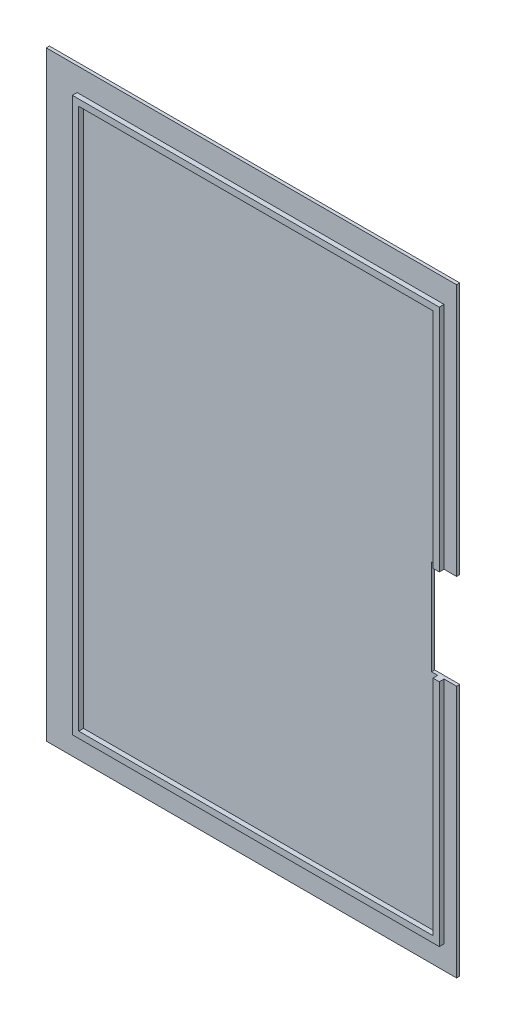
SolidWorks part; units mm, degrees
ref_plane "前视基准面" through (0, 0, 0) normal (0, 0, 1) x (1, 0, 0)
ref_plane "上视基准面" through (0, 0, 0) normal (0, 1, 0) x (1, 0, 0)
ref_plane "右视基准面" through (0, 0, 0) normal (1, 0, 0) x (0, 0, -1)
sketch "草图1" plane through (0, 0, 0) normal (0, 0, 1) x (1, 0, 0)
  line L1 (-64.75, 94.75) -> (64.75, 94.75)
  line L2 (-64.75, 94.75) -> (-64.75, -94.75)
  line L3 (-64.75, -94.75) -> (64.75, -94.75)
  line L4 (64.75, 94.75) -> (64.75, -94.75)
  line L5 (-64.75, 94.75) -> (64.75, -94.75) construction
  line L6 (-64.75, -94.75) -> (64.75, 94.75) construction
  point P0 (0, 0)
  dimension "D1" = 129.5
  dimension "D2" = 189.5
extrude "凸台-拉伸1" add sketch "草图1" along normal blind 1
sketch "草图2" plane through (0, 0, 1) normal (0, 0, 1) x (1, 0, 0)
  line L1 (-53, 85.4) -> (58.8, 85.4)
  line L2 (-53, 85.4) -> (-53, -85.4)
  line L3 (-53, -85.4) -> (58.8, -85.4)
  line L4 (58.8, 85.4) -> (58.8, -85.4)
  line L5 (-53, 85.4) -> (58.8, -85.4) construction
  line L6 (-53, -85.4) -> (58.8, 85.4) construction
  line L7 (-55, 87.4) -> (60.8, 87.4)
  line L8 (-55, 87.4) -> (-55, -87.4)
  line L9 (-55, -87.4) -> (60.8, -87.4)
  line L10 (60.8, 87.4) -> (60.8, -87.4)
  line L11 (-55, 87.4) -> (60.8, -87.4) construction
  line L12 (-55, -87.4) -> (60.8, 87.4) construction
  point P0 (2.9, 0)
  point P7 (2.9, 0)
  point P12 (0, 0)
  dimension "D1" = 111.8
  dimension "D2" = 170.8
  dimension "D3" = 2
  dimension "D4" = 2
  dimension "D5" = 2.9
extrude "凸台-拉伸2" add sketch "草图2" along normal blind 1.5
sketch "草图3" plane through (0, 0, 2.5) normal (0, 0, 1) x (1, 0, 0)
  line L0 (60.8, -87.4) -> (60.8, 87.4) construction
  line L1 (56.85, 15) -> (64.75, 15)
  line L2 (56.85, 15) -> (56.85, -15)
  line L3 (56.85, -15) -> (64.75, -15)
  line L4 (64.75, 15) -> (64.75, -15)
  line L5 (56.85, 15) -> (64.75, -15) construction
  line L6 (56.85, -15) -> (64.75, 15) construction
  line L9 (64.75, -94.75) -> (64.75, 94.75) construction
  point P0 (60.8, 0)
  dimension "D1" = 30
extrude "切除-拉伸1" cut sketch "草图3" against normal blind 3
